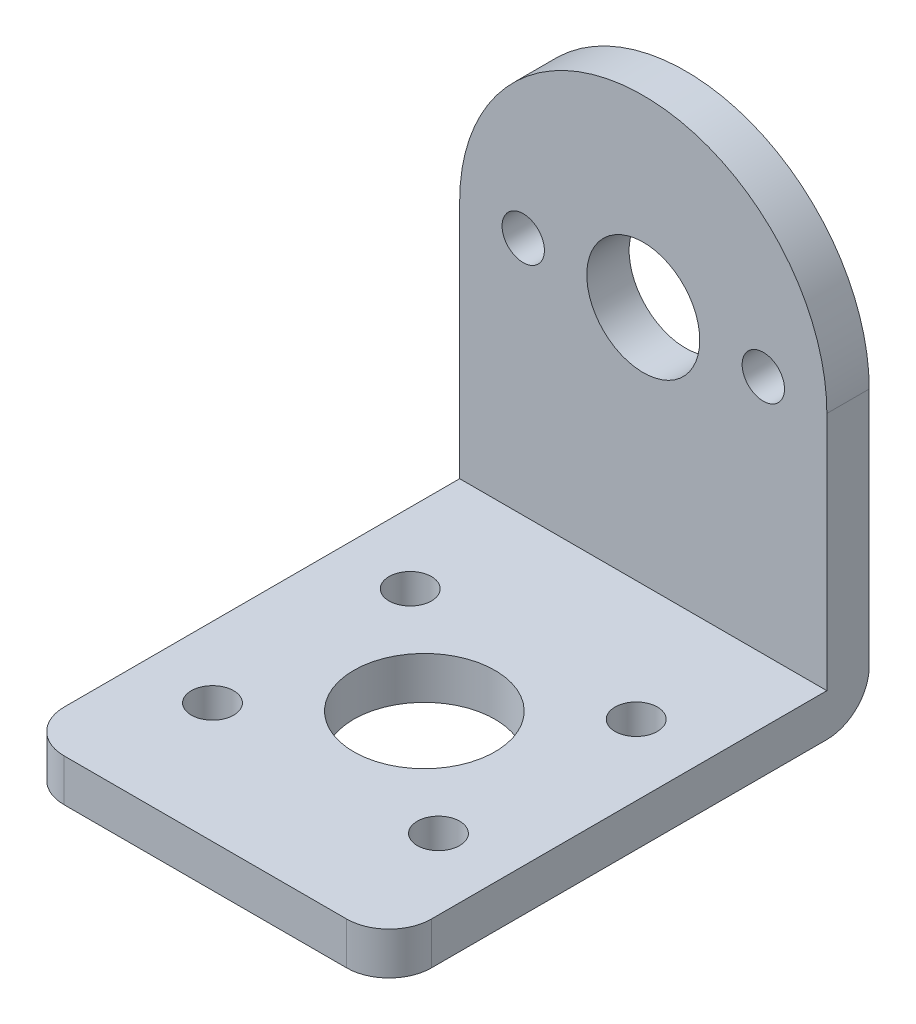
SolidWorks part; units mm, degrees
material "Ductile Iron (SN)"
ref_plane "Front Plane" through (0, 0, 0) normal (0, 0, 1) x (1, 0, 0)
ref_plane "Top Plane" through (0, 0, 0) normal (0, 1, 0) x (1, 0, 0)
ref_plane "Right Plane" through (0, 0, 0) normal (1, 0, 0) x (0, 0, -1)
sketch "Sketch2" plane through (0, 0, 0) normal (0, 0, 1) x (1, 0, 0)
  line L0 (-13, 0) -> (13, 0)
  line L1 (13, 0) -> (13, 20)
  line L3 (-13, 20) -> (-13, 0)
  arc A0 (13, 20) -> (-13, 20) centre (0, 20) ccw
  circle A1 centre (0, 20) radius 4
  circle A2 centre (-8.5, 20) radius 1.5
  circle A3 centre (8.5, 20) radius 1.5
  point P3 (0, 0)
  point P13 (0, 0)
  point P14 (0, 0)
  point P15 (0, 0)
  point P16 (-8.5, 20)
  point P17 (0, 0)
  dimension "D3" = 17
  dimension "D1" = 20
  dimension "D5" = 8
  dimension "D6" = 3
  dimension "D2" = 26
  dimension "D4" = 8.5
extrude "Boss-Extrude1" add sketch "Sketch2" along normal blind 3
sketch "Sketch3" plane through (0, 0, 3) normal (0, 0, 1) x (1, 0, 0)
  line L0 (-13, 0) -> (13, 0)
  line L1 (13, 0) -> (13, 3)
  line L2 (13, 0) -> (13, 20) construction
  line L3 (13, 3) -> (-13, 3)
  line L4 (-13, 20) -> (-13, 0) construction
  line L5 (-13, 3) -> (-13, 0)
  dimension "D1" = 3
extrude "Boss-Extrude2" add sketch "Sketch3" along normal blind 31
sketch "Sketch4" plane through (0, 3, 0) normal (0, 1, 0) x (1, 0, 0)
  line L0 (13, -34) -> (13, -3) construction
  line L1 (13, -34) -> (-13, -34) construction
  circle A0 centre (0, -18.5) radius 5
  circle A1 centre (-8, -11.5) radius 1.5
  circle A2 centre (8, -11.5) radius 1.5
  circle A3 centre (8, -25.5) radius 1.5
  circle A4 centre (-8, -25.5) radius 1.5
  point P5 (13, -18.5)
  point P8 (0, -34)
  point P16 (0, 0)
  point P17 (0, 0)
  point P18 (0, 0)
  point P19 (0, 0)
  point P20 (8.114, -25.9157)
  dimension "D1" = 10
  dimension "D2" = 16
  dimension "D6" = 3
  dimension "D3" = 14
  dimension "D4" = 7
  dimension "D5" = 8
extrude "Cut-Extrude1" cut sketch "Sketch4" against normal through all
fillet "Fillet1" radius 3 2 edges at (-13, 1.5, 34) (13, 1.5, 34)
fillet "Fillet2" radius 3 1 edges at (0, 0, 0)
